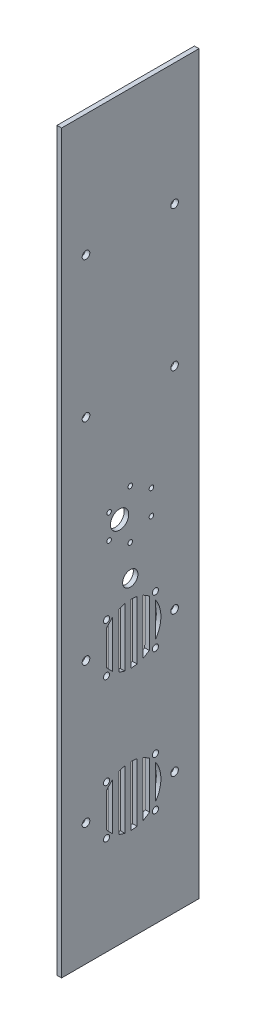
SolidWorks part; units mm, degrees
ref_plane "Alzado" through (0, 0, 0) normal (0, 0, 1) x (1, 0, 0)
ref_plane "Planta" through (0, 0, 0) normal (0, 1, 0) x (1, 0, 0)
ref_plane "Vista lateral" through (0, 0, 0) normal (1, 0, 0) x (0, 0, -1)
sketch "Croquis3" plane through (-90.5016, 0, 0) normal (-1, 0, 0) x (0, 0, 1)
  line L1 (-88, 703.6284) -> (2, 703.6284)
  line L2 (-88, 703.6284) -> (-88, 1185.6284)
  line L3 (-88, 1185.6284) -> (2, 1185.6284)
  line L4 (2, 703.6284) -> (2, 1185.6284)
  line L5 (-59.4584, 887.4218) -> (-59.4584, 864.8149)
  line L7 (-55.6419, 891.4588) -> (-55.4584, 860.6339)
  line L8 (-55.4584, 860.6339) -> (-51.4584, 858.2363)
  line L9 (-51.4584, 858.2363) -> (-51.4584, 894.0004)
  line L10 (-51.4584, 894.0004) -> (-55.6419, 891.4588)
  line L12 (-47.4584, 895.2956) -> (-47.4584, 856.941)
  line L13 (-47.4584, 856.941) -> (-43.4584, 856.5283)
  line L14 (-43.4584, 856.5283) -> (-43.4584, 895.7083)
  line L15 (-43.4584, 895.7083) -> (-47.4584, 895.2956)
  line L17 (-39.4584, 856.941) -> (-35.4584, 858.2363)
  line L18 (-35.4584, 858.2363) -> (-35.4584, 894.0004)
  line L19 (-35.4584, 894.0004) -> (-39.4584, 895.2956)
  line L20 (-39.4584, 895.2956) -> (-39.4584, 856.941)
  line L22 (-31.4584, 860.6339) -> (-31.2749, 891.4588)
  line L23 (-31.2749, 891.4588) -> (-27.4584, 887.4218)
  line L24 (-27.4584, 887.4218) -> (-27.4584, 864.8149)
  line L25 (-27.4584, 864.8149) -> (-31.4584, 860.6339)
  line L27 (-27.4584, 772.8149) -> (-31.2749, 768.7778)
  line L28 (-31.2749, 768.7778) -> (-31.4584, 799.6028)
  line L29 (-31.4584, 799.6028) -> (-27.4584, 795.4218)
  line L30 (-27.4584, 795.4218) -> (-27.4584, 772.8149)
  line L32 (-35.4584, 766.2363) -> (-39.4584, 764.941)
  line L33 (-39.4584, 764.941) -> (-39.4584, 803.2956)
  line L34 (-39.4584, 803.2956) -> (-35.4584, 802.0004)
  line L35 (-35.4584, 802.0004) -> (-35.4584, 766.2363)
  line L37 (-43.4584, 764.5283) -> (-47.4584, 764.941)
  line L38 (-47.4584, 764.941) -> (-47.4584, 803.2956)
  line L39 (-47.4584, 803.2956) -> (-43.4584, 803.7083)
  line L40 (-43.4584, 803.7083) -> (-43.4584, 764.5283)
  line L41 (-51.4584, 766.2363) -> (-55.6419, 768.7778)
  line L42 (-55.6419, 768.7778) -> (-55.4584, 799.6028)
  line L43 (-55.4584, 799.6028) -> (-51.4584, 802.0004)
  line L44 (-51.4584, 802.0004) -> (-51.4584, 766.2363)
  line L45 (-59.4584, 795.4218) -> (-59.4584, 772.8149)
  circle A25 centre (-72, 1105.6284) radius 2.5
  circle A26 centre (-14, 1105.6284) radius 2.5
  circle A27 centre (-72, 1013.6284) radius 2.5
  circle A28 centre (-14, 1013.6284) radius 2.5
  circle A29 centre (-36, 944.6284) radius 6
  circle A30 centre (-29.1368, 936.1167) radius 1.5
  circle A31 centre (-43, 928.1128) radius 1.5
  circle A32 centre (-29.1368, 952.1245) radius 1.5
  circle A33 centre (-43, 960.1284) radius 1.5
  circle A34 centre (-56.8632, 952.1245) radius 1.5
  circle A35 centre (-56.8632, 936.1167) radius 1.5
  circle A36 centre (-43, 907.7284) radius 5
  circle A37 centre (-14, 875.6284) radius 2.5
  circle A38 centre (-27.4584, 860.1183) radius 2
  circle A39 centre (-27.4584, 892.1183) radius 2
  circle A40 centre (-14, 783.6284) radius 2.5
  circle A41 centre (-27.4584, 768.1183) radius 2
  circle A42 centre (-27.4584, 800.1183) radius 2
  circle A43 centre (-59.4584, 768.1183) radius 2
  circle A44 centre (-72, 783.6284) radius 2.5
  circle A45 centre (-59.4584, 800.1183) radius 2
  circle A46 centre (-59.4584, 860.1183) radius 2
  circle A47 centre (-72, 875.6284) radius 2.5
  circle A48 centre (-59.4584, 892.1183) radius 2
  arc A49 (-59.4584, 864.8149) -> (-59.4584, 887.4218) centre (-43.4584, 876.1183) cw
  arc A50 (-59.4584, 772.8149) -> (-59.4584, 795.4218) centre (-43.4584, 784.1183) cw
  dimension "D1" = 90
extrude "Saliente-Extruir1" add sketch "Croquis3" along normal blind 3
